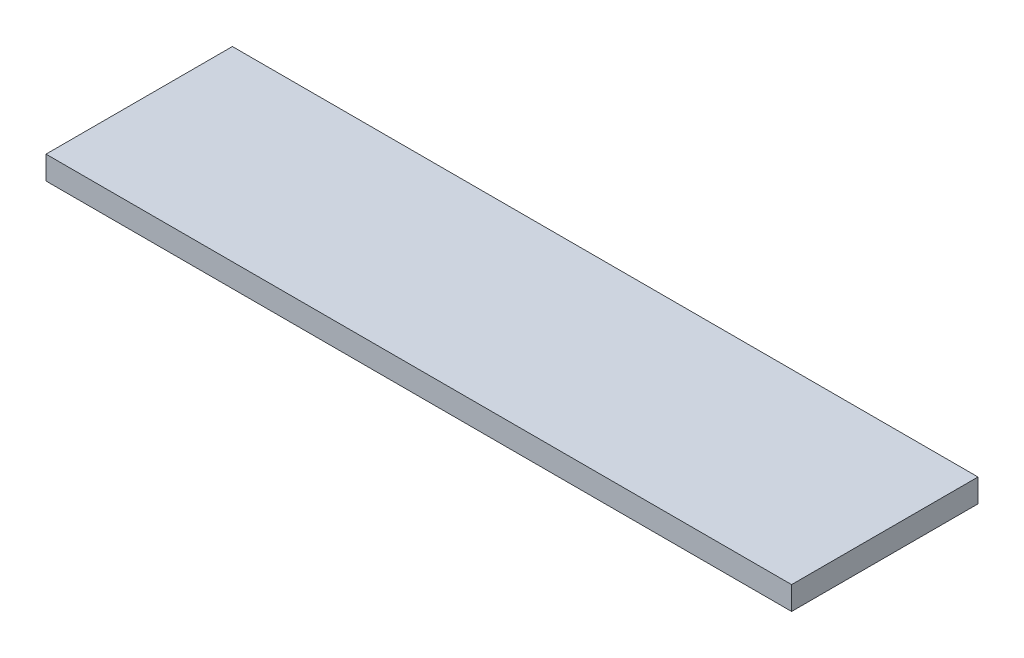
SolidWorks part; units mm, degrees
ref_plane "Front Plane" through (0, 0, 0) normal (0, 0, 1) x (1, 0, 0)
ref_plane "Top Plane" through (0, 0, 0) normal (0, 1, 0) x (1, 0, 0)
ref_plane "Right Plane" through (0, 0, 0) normal (1, 0, 0) x (0, 0, -1)
sketch "Sketch1" plane through (0, 0, 0) normal (0, 1, 0) x (1, 0, 0)
  line L1 (0, 0) -> (101.6, 0)
  line L2 (0, 0) -> (0, 25.4)
  line L3 (0, 25.4) -> (101.6, 25.4)
  line L4 (101.6, 0) -> (101.6, 25.4)
  dimension "D1" = 25.4
  dimension "D2" = 101.6
extrude "Boss-Extrude1" add sketch "Sketch1" along normal blind 3.175
